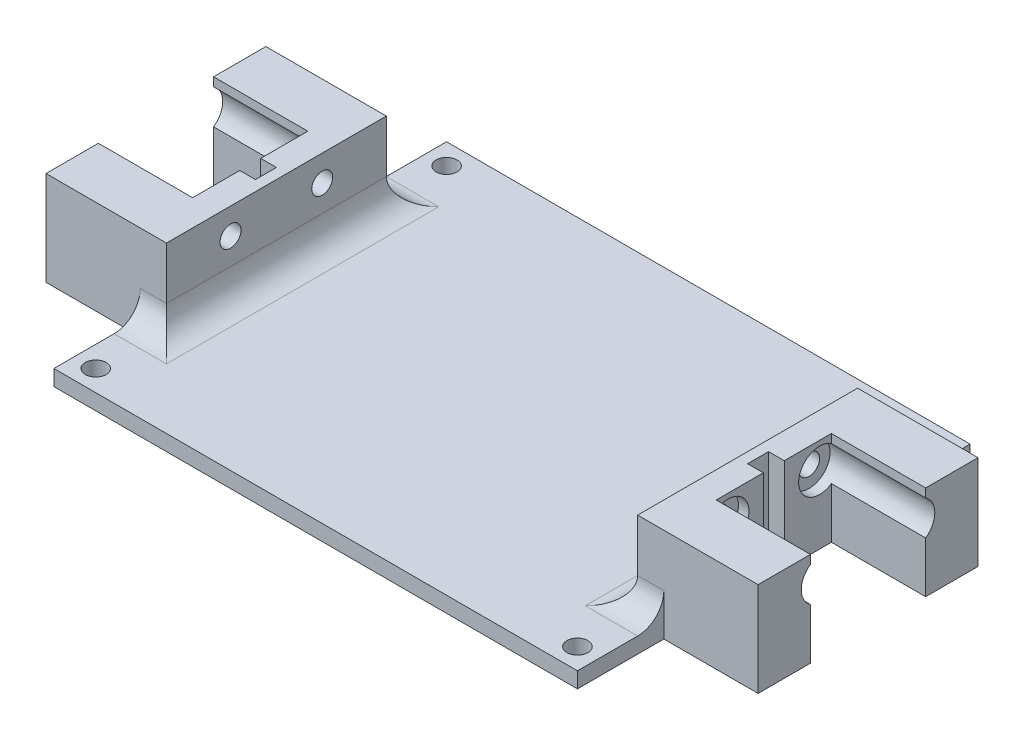
SolidWorks part; units mm, degrees
material "Nylon 101"
ref_plane "Front Plane" through (0, 0, 0) normal (0, 0, 1) x (1, 0, 0)
ref_plane "Top Plane" through (0, 0, 0) normal (0, 1, 0) x (1, 0, 0)
ref_plane "Right Plane" through (0, 0, 0) normal (1, 0, 0) x (0, 0, -1)
sketch "Sketch1" plane through (0, 0, 0) normal (0, 1, 0) x (1, 0, 0)
  line L0 (50, 2) -> (50, 11)
  line L1 (-50, -37.5) -> (50, -37.5)
  line L2 (-50, -37.5) -> (-50, -21)
  line L3 (-50, 37.5) -> (50, 37.5)
  line L4 (50, -37.5) -> (50, -21)
  line L5 (-50, -37.5) -> (50, 37.5) construction
  line L6 (-50, 37.5) -> (50, -37.5) construction
  line L9 (50, 21) -> (68, 21)
  line L10 (68, -21) -> (68, -11)
  line L11 (47, 2) -> (50, 2)
  line L12 (47, 2) -> (47, -2)
  line L13 (50, -11) -> (68, -11)
  line L17 (50, 0) -> (68, 11) construction
  line L18 (50, 0) -> (68, -11) construction
  line L19 (50, 0) -> (68, -21) construction
  line L20 (50, 11) -> (68, 11)
  line L21 (50, 0) -> (68, 21) construction
  line L22 (50, -21) -> (68, -21)
  line L23 (68, 11) -> (68, 21)
  line L24 (50, -11) -> (50, -2)
  line L25 (50, 21) -> (50, 37.5)
  line L26 (47, -2) -> (50, -2)
  line L28 (47, 2) -> (50, 0) construction
  line L29 (47, -2) -> (50, 0) construction
  line L30 (0, -37.5) -> (0, 37.5) construction
  line L31 (-68, -21) -> (-68, -11)
  line L32 (-50, -21) -> (-68, -21)
  line L33 (-50, -11) -> (-68, -11)
  line L34 (-47, -2) -> (-50, -2)
  line L35 (-47, 2) -> (-47, -2)
  line L36 (-47, 2) -> (-50, 2)
  line L37 (-68, 11) -> (-68, 21)
  line L38 (-50, 11) -> (-68, 11)
  line L39 (-50, 21) -> (-68, 21)
  line L40 (-50, 21) -> (-50, 37.5)
  line L41 (-50, 2) -> (-50, 11)
  line L42 (-50, -11) -> (-50, -2)
  point P0 (0, 0)
  point P6 (50, 0)
  point P11 (50, 0)
  dimension "D1" = 75
  dimension "D2" = 100
  dimension "D3" = 10
  dimension "D4" = 18
  dimension "D5" = 22
  dimension "D6" = 11
  dimension "D7" = 10
  dimension "D8" = 4
  dimension "D9" = 3
extrude "Boss-Extrude1" add sketch "Sketch1" along normal blind 3
sketch "Sketch2" plane through (0, 3, 0) normal (0, 1, 0) x (1, 0, 0)
  line L0 (-68, 11) -> (-68, 21)
  line L1 (-68, 21) -> (-45, 21)
  line L2 (-68, 11) -> (-50, 11)
  line L3 (-50, 11) -> (-50, 2)
  line L4 (-50, 2) -> (-47, 2)
  line L5 (-47, 2) -> (-47, -2)
  line L6 (-47, -2) -> (-50, -2)
  line L7 (-50, -2) -> (-50, -11)
  line L8 (-50, -11) -> (-68, -11)
  line L9 (-68, -11) -> (-68, -21)
  line L10 (-68, -21) -> (-45, -21)
  line L11 (-45, -21) -> (-45, 21)
  line L12 (0, 0) -> (0, 37.5) construction
  line L13 (50, 37.5) -> (-50, 37.5) construction
  line L14 (45, -21) -> (45, 21)
  line L15 (68, -21) -> (45, -21)
  line L16 (68, -11) -> (68, -21)
  line L17 (50, -11) -> (68, -11)
  line L18 (50, -2) -> (50, -11)
  line L19 (47, -2) -> (50, -2)
  line L20 (47, 2) -> (47, -2)
  line L21 (50, 2) -> (47, 2)
  line L22 (50, 11) -> (50, 2)
  line L23 (68, 11) -> (50, 11)
  line L24 (68, 21) -> (45, 21)
  line L25 (68, 11) -> (68, 21)
  dimension "D1" = 5
extrude "Boss-Extrude2" add sketch "Sketch2" along normal blind 15
sketch "Sketch3" plane through (-50, 0, 0) normal (-1, 0, 0) x (0, 0, 1)
  line L0 (0, 0) -> (0, 18) construction
  line L1 (-2, 18) -> (2, 18) construction
  line L2 (-7.1834, 9.6872) -> (6.5963, 9.6872) construction
  circle A0 centre (-8.75, 13.0294) radius 2
  circle A1 centre (8.75, 13.0294) radius 2
  dimension "D1" = 4
  dimension "D2" = 17.5
  dimension "D3" = 8.75
extrude "Cut-Extrude1" cut sketch "Sketch3" against normal through all
sketch "Sketch5" plane through (68, 0, 0) normal (1, 0, 0) x (0, 0, -1)
  circle A2 centre (-8.75, 13.0294) radius 4
  circle A3 centre (-8.75, 13.0294) radius 4
  circle A5 centre (8.75, 13.0294) radius 4
  circle A6 centre (8.75, 13.0294) radius 4
  dimension "D1" = 2
  dimension "D2" = 2
extrude "Cut-Extrude3" cut sketch "Sketch5" against normal blind 20
sketch "Sketch6" plane through (-68, 0, 0) normal (-1, 0, 0) x (0, 0, 1)
  circle A2 centre (8.75, 13.0294) radius 4
  circle A3 centre (8.75, 13.0294) radius 4
  circle A5 centre (-8.75, 13.0294) radius 4
  circle A6 centre (-8.75, 13.0294) radius 4
  dimension "D1" = 2
  dimension "D2" = 2
extrude "Cut-Extrude4" cut sketch "Sketch6" against normal blind 20
fillet "Fillet1" radius 5 6 edges at (-47.5, 3, 21) (-45, 3, 0) (-47.5, 3, -21) (47.5, 3, 21) (45, 3, 0) (47.5, 3, -21)
sketch "Sketch7" plane through (0, 3, 0) normal (0, 1, 0) x (1, 0, 0)
  line L0 (50, 37.5) -> (-50, 37.5) construction
  line L1 (50, 26) -> (50, 37.5) construction
  line L2 (-50, 37.5) -> (-50, 26) construction
  line L3 (-50, -37.5) -> (50, -37.5) construction
  line L4 (-50, -26) -> (-50, -37.5) construction
  line L5 (50, -37.5) -> (50, -26) construction
  circle A0 centre (46, 33.5) radius 2
  circle A1 centre (-46, 33.5) radius 2
  circle A2 centre (46, -33.5) radius 2
  circle A3 centre (-46, -33.5) radius 2
  dimension "D1" = 4
  dimension "D3" = 4
  dimension "D2" = 4
  dimension "D4" = 4
  dimension "D5" = 4
  dimension "D6" = 4
  dimension "D7" = 4
  dimension "D8" = 4
  dimension "D9" = 4
extrude "Cut-Extrude5" cut sketch "Sketch7" against normal blind 20
equation "\"D3@Sketch3\"=\"D2@Sketch3\"/2"
